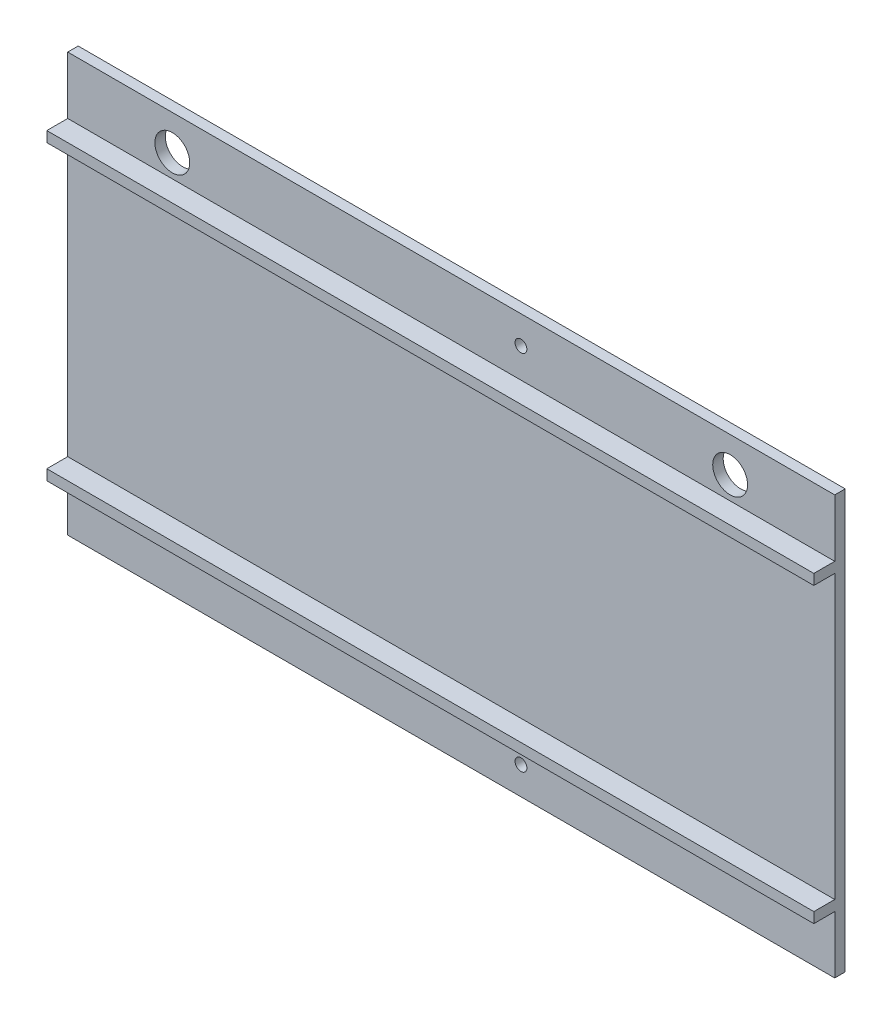
SolidWorks part; units mm, degrees
ref_plane "前视基准面" through (0, 0, 0) normal (0, 0, 1) x (1, 0, 0)
ref_plane "上视基准面" through (0, 0, 0) normal (0, 1, 0) x (1, 0, 0)
ref_plane "右视基准面" through (0, 0, 0) normal (1, 0, 0) x (0, 0, -1)
other "Configuration Table"
sketch "草图1" plane through (0, 0, 0) normal (0, 0, 1) x (1, 0, 0)
  line L1 (-110, -60) -> (110, -60)
  line L2 (-110, -60) -> (-110, 60)
  line L3 (-110, 60) -> (110, 60)
  line L4 (110, -60) -> (110, 60)
  dimension "D1" = 220
  dimension "D2" = 120
extrude "Lid" add sketch "草图1" along normal blind 3 from offset 40 separate body
sketch "草图2" plane through (0, 0, 0) normal (0, 0, 1) x (1, 0, 0)
  line L1 (-110, -43.5) -> (110, -43.5)
  line L2 (-110, -43.5) -> (-110, -40.5)
  line L3 (-110, -40.5) -> (110, -40.5)
  line L4 (110, -43.5) -> (110, -40.5)
  dimension "D1" = 220
  dimension "D2" = 3
extrude "Rail" add sketch "草图2" along normal blind 9 from offset 40
sketch "草图3" plane through (0, 0, 0) normal (0, 0, 1) x (1, 0, 0)
  line L1 (-110, 40.5) -> (110, 40.5)
  line L2 (-110, 40.5) -> (-110, 43.5)
  line L3 (-110, 43.5) -> (110, 43.5)
  line L4 (110, 40.5) -> (110, 43.5)
  dimension "D1" = 220
  dimension "D2" = 3
extrude "凸台-拉伸3" add sketch "草图3" along normal blind 9 from offset 40
sketch "草图4" plane through (0, 0, 0) normal (0, 0, 1) x (1, 0, 0)
  circle A0 centre (-80, 50) radius 5
  dimension "D1" = 10
extrude "CableHole" cut sketch "草图4" along normal blind 5 from offset 39
sketch "草图5" plane through (0, 0, 0) normal (0, 0, 1) x (1, 0, 0)
  circle A0 centre (80, 50) radius 5
  dimension "D1" = 10
extrude "切除-拉伸2" cut sketch "草图5" along normal blind 5 from offset 39
sketch "草图6" plane through (0, 0, 0) normal (0, 0, 1) x (1, 0, 0)
  circle A0 centre (20, -52) radius 1.7
  dimension "D1" = 3.4
extrude "TowerScrew" cut sketch "草图6" along normal blind 5 from offset 39
sketch "草图7" plane through (0, 0, 0) normal (0, 0, 1) x (1, 0, 0)
  circle A0 centre (20, 52) radius 1.7
  dimension "D1" = 3.4
extrude "切除-拉伸4" cut sketch "草图7" along normal blind 5 from offset 39
